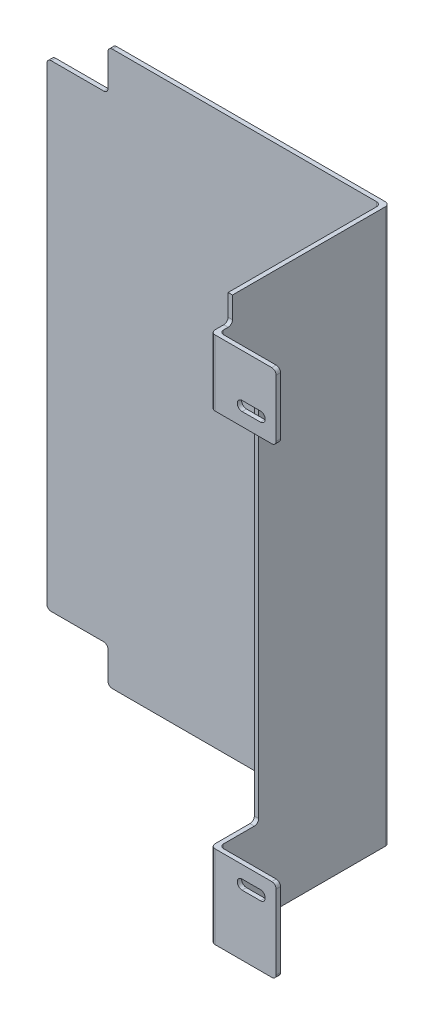
SolidWorks part; units mm, degrees
ref_plane "前视基准面" through (0, 0, 0) normal (0, 0, 1) x (1, 0, 0)
ref_plane "上视基准面" through (0, 0, 0) normal (0, 1, 0) x (1, 0, 0)
ref_plane "右视基准面" through (0, 0, 0) normal (1, 0, 0) x (0, 0, -1)
sketch "草图1" plane through (0, 0, 0) normal (0, 0, 1) x (1, 0, 0)
  line L1 (-145.1182, 70.3029) -> (-67.6182, 70.3029)
  line L2 (-145.1182, 70.3029) -> (-145.1182, -56.6971)
  line L3 (-145.1182, -56.6971) -> (-67.6182, -56.6971)
  line L4 (-67.6182, 70.3029) -> (-67.6182, -56.6971)
  dimension "D1" = 77.5
  dimension "D2" = 127
extrude "凸台-拉伸1" add sketch "草图1" along normal blind 1
sketch "草图3" plane through (0, 0, 1) normal (0, 0, 1) x (1, 0, 0)
  line L0 (-145.1182, -56.6971) -> (-67.6182, -56.6971) construction
  line L7 (-67.6182, -56.6971) -> (-68.6182, -56.6971)
  line L8 (-67.6182, -56.6971) -> (-67.6182, 70.3029)
  line L9 (-67.6182, 70.3029) -> (-68.6182, 70.3029)
  line L10 (-68.6182, -56.6971) -> (-68.6182, 70.3029)
  dimension "D1" = 1
  dimension "D2" = 127
extrude "凸台-拉伸3" add sketch "草图3" along normal blind 39
sketch "草图8" plane through (0, 0, 40) normal (0, 0, 1) x (1, 0, 0)
  line L5 (-68.6182, -56.6971) -> (-53.6182, -56.6971)
  line L6 (-68.6182, -56.6971) -> (-68.6182, 70.3029)
  line L7 (-68.6182, 70.3029) -> (-53.6182, 70.3029)
  line L8 (-53.6182, -56.6971) -> (-53.6182, 70.3029)
extrude "凸台-拉伸4" add sketch "草图8" against normal blind 1
sketch "草图18" [suppressed] plane through (0, 0, 1) normal (0, 0, 1) x (1, 0, 0)
  parabola Q0 (-101.9313, -4.3681) -> (-97.8806, -5.3796) focus (-98.4724, -7.7523) apex (-96.7936, -6.2931)
  parabola Q1 (-114.4565, -3.9194) -> (-115.4039, -4.354) focus (-114.2938, -11.4963) apex (-118.8736, -6.8028)
  parabola Q2 (-115.4039, -4.354) -> (-120.029, -8.0887) focus (-114.2938, -11.4963) apex (-118.8736, -6.8028)
  spline S0 degree 3 poles (-89.7456, -20.7504) (-89.1125, -20.9983) (-87.8283, -21.4248) (-87.4235, -22.4556) (-87.2755, -23.5186) knots 0 0 0 0 0.446139 1 1 1 1
  spline S1 degree 3 poles (-89.7456, -20.7504) (-97.5984, -17.5865) (-109.0806, -11.6152) (-112.2331, -8.9433) knots -4 -4 -4 -4 -3 -3 -3 -3
  spline S2 degree 3 poles (-112.2331, -8.9433) (-108.9755, -7.7227) (-105.5025, -6.6266) (-101.9453, -7.1887) knots 0 0 0 0 1 1 1 1
  spline S3 degree 3 poles (-101.9453, -7.1887) (-98.8126, -8.1278) (-97.3159, -11.0038) (-95.3518, -14.4543) knots 0 0 0 0 1 1 1 1
  spline S4 degree 3 poles (-95.3518, -14.4543) (-98.957, -13.4047) (-102.5971, -12.4775) (-106.196, -11.4058) knots 4 4 4 4 5 5 5 5
  spline S5 degree 3 poles (-106.196, -11.4058) (-100.5485, -14.2329) (-94.849, -16.9749) (-88.9366, -19.2222) knots 0 0 0 0 0.995408 0.995408 0.995408 0.995408
  spline S6 degree 3 poles (-97.8806, -5.3796) (-97.8472, -5.4044) (-97.8139, -5.4295) (-97.6009, -5.5916) (-97.4239, -5.7339) (-97.0786, -6.0276) (-96.9102, -6.1792) (-96.5841, -6.4876) (-96.4268, -6.6438) (-96.1223, -6.9579) (-95.9753, -7.115) (-95.6859, -7.433) (-95.5442, -7.5934) (-95.2653, -7.9173) (-95.1279, -8.081) (-94.8582, -8.4107) (-94.7257, -8.5768) (-94.3352, -9.0785) (-94.0839, -9.4177) (-93.3551, -10.4466) (-92.902, -11.1481) (-92.2604, -12.2155) (-92.0529, -12.5739) (-91.6485, -13.2946) (-91.4516, -13.6568) (-91.163, -14.2025) (-91.0678, -14.3847) (-90.8796, -14.7496) (-90.7862, -14.9327) (-90.6011, -15.3009) (-90.5093, -15.4859) (-90.3279, -15.8573) (-90.2382, -16.0439) (-89.9724, -16.6076) (-89.7998, -16.9887) (-89.5524, -17.57) (-89.3912, -17.9607) (-89.161, -18.5633) (-89.0179, -18.9746) (-88.9465, -19.1919) (-88.9444, -19.1983) (-88.9413, -19.2079) (-88.9402, -19.2111) (-88.9383, -19.2169) (-88.9374, -19.2196) (-88.9366, -19.2222) knots 0.239307 0.239307 0.239307 0.239307 0.240445 0.240445 0.246621 0.246621 0.252796 0.252796 0.258972 0.258972 0.265148 0.265148 0.271323 0.271323 0.277499 0.277499 0.283675 0.283675 0.296026 0.296026 0.320729 0.320729 0.33308 0.33308 0.345431 0.345431 0.351607 0.351607 0.357783 0.357783 0.363958 0.363958 0.370134 0.370134 0.382485 0.382485 0.388661 0.394837 0.401205 0.401205 0.401398 0.401398 0.401495 0.401495 0.401574 0.401574 0.401574 0.401574
  spline S7 degree 3 poles (-116.6018, -8.849) (-116.5998, -8.8474) (-116.5974, -8.8456) (-116.5927, -8.8419) (-116.59, -8.8398) (-116.5821, -8.8337) (-116.5768, -8.8296) (-116.4817, -8.7559) (-116.3046, -8.624) (-116.1228, -8.4987) (-115.8554, -8.3214) (-115.6731, -8.2097) (-115.3028, -7.9997) (-115.1148, -7.9014) (-114.7363, -7.7174) (-114.5458, -7.6317) (-114.1653, -7.471) (-113.9754, -7.3959) (-113.6933, -7.2894) (-113.5061, -7.2203) (-113.3212, -7.1544) (-113.1382, -7.0899) (-113.0474, -7.0582) (-112.868, -6.9959) (-112.7787, -6.965) (-112.51, -6.8721) (-112.3304, -6.8105) (-111.9702, -6.6879) (-111.7895, -6.627) (-111.246, -6.4459) (-110.8815, -6.3273) (-110.1481, -6.0972) (-109.7792, -5.9856) (-109.0377, -5.7713) (-108.6652, -5.6687) (-107.9174, -5.4732) (-107.5421, -5.3804) (-106.7896, -5.2045) (-106.4124, -5.1215) (-105.6568, -4.9645) (-105.0891, -4.8536) (-104.5204, -4.752) (-104.1411, -4.6862) (-103.9514, -4.6542) (-103.6665, -4.6076) (-103.5716, -4.5923) (-103.3816, -4.5621) (-103.2867, -4.5473) (-102.9994, -4.503) (-102.8049, -4.4744) (-102.5087, -4.4344) (-102.3096, -4.4088) (-102.1072, -4.386) (-101.9806, -4.373) (-101.9559, -4.3705) (-101.9313, -4.3681) knots 0.042262 0.042262 0.042262 0.042262 0.042342 0.042342 0.042438 0.042438 0.042631 0.042631 0.045912 0.049 0.049 0.055175 0.055175 0.061351 0.061351 0.067527 0.067527 0.073702 0.073702 0.07679 0.079878 0.079878 0.082966 0.082966 0.086054 0.086054 0.092229 0.092229 0.098405 0.098405 0.110756 0.110756 0.123108 0.123108 0.135459 0.135459 0.14781 0.14781 0.160162 0.160162 0.172513 0.178689 0.178689 0.184864 0.184864 0.187952 0.187952 0.19104 0.19104 0.197216 0.197216 0.200303 0.203391 0.203391 0.204134 0.204134 0.204134 0.204134
  spline S8 degree 3 poles (-116.6018, -8.849) (-110.3978, -13.2932) (-105.2514, -16.5827) (-96.9265, -21.1645) (-92.6363, -22.9227) (-87.2755, -23.5186) knots 0.00164 0.00164 0.00164 0.00164 0.530572 0.630572 1 1 1 1
  spline S9 degree 3 poles (-88.7365, -27.2498) (-94.4739, -26.6711) (-109.3773, -17.828) (-117.4293, -10.1662) knots 0 0 0 0 1 1 1 1
  spline S10 degree 3 poles (-103.2928, -25.5158) (-96.384, -27.8093) (-90.5454, -27.6666) (-88.7365, -27.2498) knots 0 0 0 0 1 1 1 1
  spline S11 degree 3 poles (-117.9989, -12.9847) (-110.4635, -20.3444) (-105.7541, -24.6554) (-103.2928, -25.5158) knots 4 4 4 4 5 5 5 5
  spline S12 degree 3 poles (-125.2457, -15.8822) (-121.0594, -13.857) (-118.3948, -12.7844) (-117.9989, -12.9847) knots 0 0 0 0 1 1 1 1
  spline S13 degree 3 poles (-117.4293, -10.1662) (-117.889, -9.907) (-118.6277, -8.7081) (-117.4404, -7.5431) knots 0 0 0 0 1 1 1 1
  spline S14 degree 3 poles (-117.4404, -7.5431) (-116.5182, -6.279) (-115.5445, -5.0513) (-114.4565, -3.9194) knots 0 0 0 0 1 1 1 1
  spline S15 degree 3 poles (-120.029, -8.0887) (-121.7599, -10.5726) (-123.6828, -13.2868) (-125.2457, -15.8822) knots 0 0 0 0 1 1 1 1
  spline S16 degree 3 poles (-131.211, -17.2541) (-128.9939, -11.3665) (-128.1543, -10.8845) (-121.5681, -9.042) knots 0 0 0 0 1 1 1 1
  spline S17 degree 3 poles (-131.211, -17.2541) (-128.1748, -14.3132) (-124.8752, -11.6665) (-121.5681, -9.042) knots 0 0 0 0 1 1 1 1
extrude "切除-拉伸3" [suppressed] cut sketch "草图18" against normal blind 10
sketch "草图19" [suppressed] plane through (0, 0, 0) normal (0, 0, -1) x (-1, 0, 0)
  line L0 (131.1182, 23.1657) -> (73.5257, 23.1657) construction
  line L1 (121.1182, 33.2479) -> (81.2098, 33.2479) construction
  line L2 (145.1182, 70.3029) -> (145.1182, -56.6971) construction
  text T0 "<b>REPUBLICE OF</b>" font "Earth Orbiter Laser" height 3.5
  text T1 "GAMERS" font "Earth Orbiter Laser" height 3.5
  dimension "D1" = 14
  dimension "D2" = 24
extrude "切除-拉伸4" [suppressed] cut sketch "草图19" against normal blind 10
sketch "草图21" plane through (0, 0, 0) normal (0, 0, -1) x (-1, 0, 0)
  line L1 (145.1182, -56.6971) -> (131.1182, -56.6971)
  line L2 (145.1182, -56.6971) -> (145.1182, -48.2971)
  line L3 (145.1182, -48.2971) -> (131.1182, -48.2971)
  line L4 (131.1182, -56.6971) -> (131.1182, -48.2971)
  line L5 (145.1182, 70.3029) -> (131.1182, 70.3029)
  line L6 (145.1182, 70.3029) -> (145.1182, 60.9029)
  line L7 (145.1182, 60.9029) -> (131.1182, 60.9029)
  line L8 (131.1182, 70.3029) -> (131.1182, 60.9029)
extrude "切除-拉伸6" cut sketch "草图21" against normal blind 10
sketch "草图23" plane through (0, 0, 0) normal (0, 0, -1) x (-1, 0, 0)
  line L0 (131.1182, -56.6971) -> (67.6182, -56.6971) construction
  line L1 (156.3685, -79.7746) -> (53.3248, -79.7746)
  line L2 (156.3685, -79.7746) -> (156.3685, -56.5971)
  line L3 (156.3685, -56.5971) -> (53.3248, -56.5971)
  line L4 (53.3248, -79.7746) -> (53.3248, -56.5971)
  line L5 (55.2439, 91.4612) -> (160.5021, 91.4612)
  line L6 (55.2439, 91.4612) -> (55.2439, 70.2029)
  line L7 (55.2439, 70.2029) -> (160.5021, 70.2029)
  line L8 (160.5021, 91.4612) -> (160.5021, 70.2029)
  line L9 (67.6182, 70.3029) -> (131.1182, 70.3029) construction
  dimension "D1" = 0.1
  dimension "D2" = 0.1
extrude "切除-拉伸7" cut sketch "草图23" against normal blind 100
sketch "草图24" plane through (0, 0, 40) normal (0, 0, 1) x (1, 0, 0)
  line L0 (-53.6182, -56.5971) -> (-53.6182, 70.3029) construction
  line L1 (-53.6182, -37.5971) -> (-68.6182, -37.5971)
  line L2 (-53.6182, -37.5971) -> (-53.6182, 49.2029)
  line L3 (-53.6182, 49.2029) -> (-68.6182, 49.2029)
  line L4 (-68.6182, -37.5971) -> (-68.6182, 49.2029)
  line L5 (-68.6182, 70.2029) -> (-68.6182, -56.5971) construction
  line L6 (-53.6182, -56.5971) -> (-68.6182, -56.5971) construction
  line L7 (-68.6182, 70.2029) -> (-55.2439, 70.2029) construction
  dimension "D1" = 19
  dimension "D2" = 21
extrude "切除-拉伸8" cut sketch "草图24" against normal blind 10
sketch "草图25" plane through (0, 0, 40) normal (0, 0, 1) x (1, 0, 0)
  line L0 (-68.6182, 70.2029) -> (-68.6182, 49.2029) construction
  line L1 (-53.6182, 70.3029) -> (-68.6182, 70.3029)
  line L2 (-53.6182, 70.3029) -> (-53.6182, 64.3029)
  line L3 (-53.6182, 64.3029) -> (-68.6182, 64.3029)
  line L4 (-68.6182, 70.3029) -> (-68.6182, 64.3029)
extrude "切除-拉伸9" cut sketch "草图25" against normal blind 4
sketch "草图26" plane through (0, 0, 39) normal (0, 0, -1) x (-1, 0, 0)
  line L1 (67.6182, -56.5971) -> (67.6182, 70.2029) construction
  line L2 (53.6182, -37.5971) -> (67.6182, -37.5971) construction
  line L3 (67.6182, 49.2029) -> (53.6182, 49.2029) construction
  line L4 (57.2182, -41.5971) -> (61.4182, -41.5971) construction
  line L5 (57.2182, -40.4971) -> (61.4182, -40.4971)
  line L6 (57.2182, -42.6971) -> (61.4182, -42.6971)
  line L8 (67.6182, -37.5971) -> (67.6182, -56.5971) construction
  line L10 (57.2182, 53.3029) -> (61.4182, 53.3029) construction
  line L11 (57.2182, 54.4029) -> (61.4182, 54.4029)
  line L12 (57.2182, 52.2029) -> (61.4182, 52.2029)
  arc A2 (57.2182, -40.4971) -> (57.2182, -42.6971) centre (57.2182, -41.5971) ccw
  arc A3 (61.4182, -42.6971) -> (61.4182, -40.4971) centre (61.4182, -41.5971) ccw
  arc A4 (57.2182, 54.4029) -> (57.2182, 52.2029) centre (57.2182, 53.3029) ccw
  arc A5 (61.4182, 52.2029) -> (61.4182, 54.4029) centre (61.4182, 53.3029) ccw
  point P7 (59.3182, 53.3029)
  point P10 (59.3182, -41.5971)
  dimension "D1" = 4.1
  dimension "D3" = 4
  dimension "D2" = 10.4
  dimension "D4" = 10.4
extrude "切除-拉伸10" cut sketch "草图26" against normal blind 3
fillet "圆角4" radius 1 19 edges at (-131.1182, -48.2971, 0.5) (-131.1182, 60.9029, 0.5) (-145.1182, 60.9029, 0.5) (-145.1182, -48.2971, 0.5) (-53.6182, -37.5971, 39.5) (-53.6182, -56.5971, 39.5) (-68.1182, 64.3029, 36) (-53.6182, 64.3029, 39.5) (-53.6182, 49.2029, 39.5) (-68.1182, 49.2029, 30) (-68.1182, -37.5971, 30) (-67.6182, 56.7529, 39) (-68.6182, 56.7529, 40) (-68.6182, -47.0971, 40) (-67.6182, -47.0971, 39) (-68.6182, 6.8029, 1) (-67.6182, 6.8029, 0) (-131.1182, -56.5971, 0.5) (-131.1182, 70.2029, 0.5)
sketch "草图27" plane through (0, 0, 0) normal (0, 0, -1) x (-1, 0, 0)
  line L0 (130.1182, -56.5971) -> (68.6182, -56.5971) construction
  line L3 (145.1182, 6.8029) -> (68.6182, 6.8029) construction
  line L4 (106.4552, -56.5971) -> (106.4552, 70.2029) construction
  line L5 (68.6182, 70.2029) -> (130.1182, 70.2029) construction
  line L7 (145.1182, 59.9029) -> (145.1182, -47.2971) construction
  line L8 (68.6182, 70.2029) -> (68.6182, -56.5971) construction
  line L9 (133.0013, 10.433) -> (75.699, 10.433) construction
  line L10 (133.0013, 27.9722) -> (75.699, 27.9722) construction
  text T0 "OMINIS" font "Earth Orbiter Laser" height 7
  text T1 "OTAKU\r\nMINI\r\nSERVICE" font "Century Gothic" height 3
  point P15 (75.699, 27.8028)
extrude "切除-拉伸11" cut sketch "草图27" against normal blind 0.2
